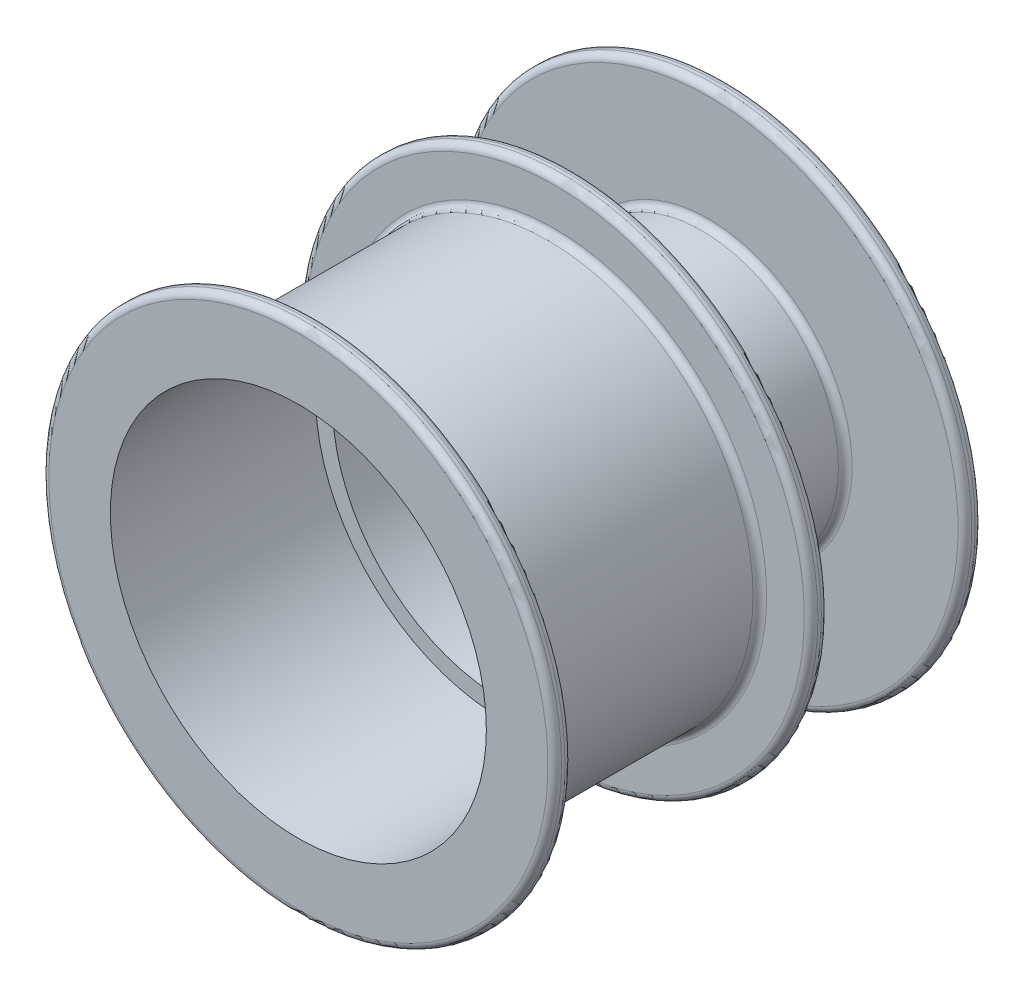
SolidWorks part; units mm, degrees
material "6061 Alloy"
ref_plane "Front" through (0, 0, 0) normal (0, 0, 1) x (1, 0, 0)
ref_plane "Top" through (0, 0, 0) normal (0, 1, 0) x (1, 0, 0)
ref_plane "Right" through (0, 0, 0) normal (1, 0, 0) x (0, 0, -1)
sketch "Sketch1" plane through (0, 0, 0) normal (1, 0, 0) x (0, 0, -1)
  line L0 (-1.9585, 0) -> (79.4204, 0) construction
  line L1 (0, 47.625) -> (0, 34.925)
  line L2 (0, 34.925) -> (38.1, 34.925)
  line L3 (38.1, 34.925) -> (38.1, 31.75)
  line L4 (38.1, 31.75) -> (47.625, 31.75)
  line L5 (47.625, 31.75) -> (47.625, 6.35)
  line L6 (47.625, 6.35) -> (55.118, 6.35)
  line L7 (55.118, 6.35) -> (55.118, 22.225)
  line L8 (55.118, 22.225) -> (79.375, 22.225)
  line L9 (0, 47.625) -> (3.175, 47.625)
  line L10 (3.175, 47.625) -> (3.175, 38.1)
  line L11 (3.175, 38.1) -> (47.625, 38.1)
  line L12 (47.625, 38.1) -> (47.625, 47.625)
  line L13 (47.625, 47.625) -> (50.8, 47.625)
  line L14 (50.8, 47.625) -> (50.8, 25.4)
  line L15 (50.8, 25.4) -> (76.2, 25.4)
  line L16 (76.2, 25.4) -> (76.2, 47.625)
  line L17 (76.2, 47.625) -> (79.375, 47.625)
  line L18 (79.375, 47.625) -> (79.375, 22.225)
  dimension "D1" = 69.85
  dimension "D2" = 63.5
  dimension "D3" = 12.7
  dimension "D4" = 44.45
  dimension "D5" = 95.25
  dimension "D6" = 3.175
  dimension "D7" = 76.2
  dimension "D8" = 44.45
  dimension "D9" = 79.375
  dimension "D10" = 9.525
  dimension "D11" = 50.8
  dimension "D12" = 25.4
  dimension "D13" = 21.082
revolve "Revolve1" add sketch "Sketch1" angle 360 about L0
fillet "Fillet1" radius 1.27 6 edges at (47.625, 0, -3.175) (47.625, 0, -47.625) (47.625, 0, -50.8) (47.625, 0, -76.2) (47.625, 0, -79.375) (47.625, 0, 0)
fillet "Fillet2" radius 1.27 4 edges at (38.1, 0, -3.175) (38.1, 0, -47.625) (25.4, 0, -50.8) (25.4, 0, -76.2)
